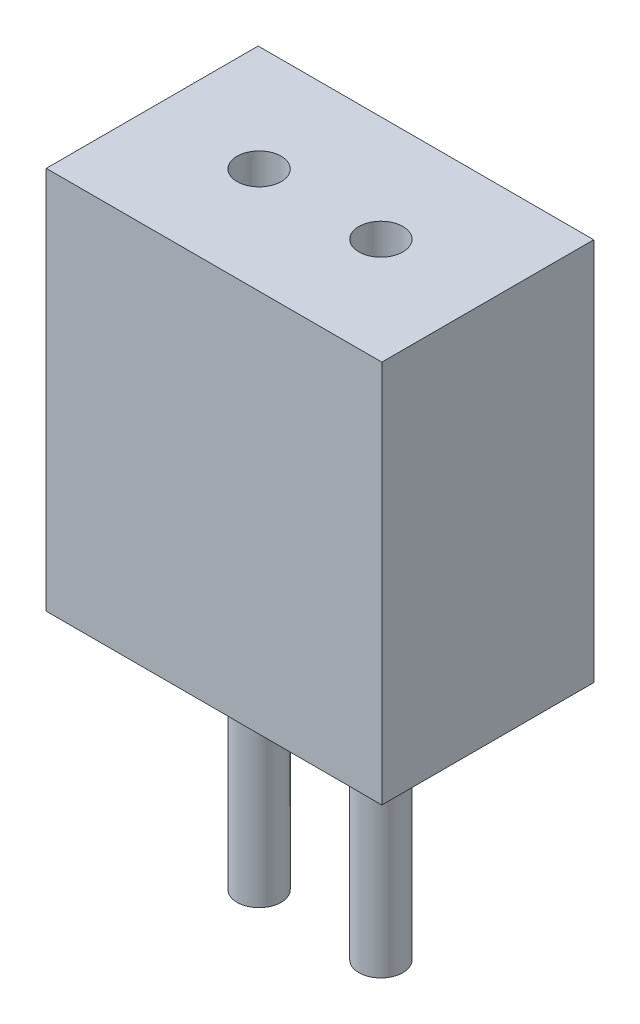
SolidWorks part; units mm, degrees
ref_plane "Front Plane" through (0, 0, 0) normal (0, 0, 1) x (1, 0, 0)
ref_plane "Top Plane" through (0, 0, 0) normal (0, 1, 0) x (1, 0, 0)
ref_plane "Right Plane" through (0, 0, 0) normal (1, 0, 0) x (0, 0, -1)
sketch "Sketch1" plane through (0, 0, 0) normal (0, 1, 0) x (1, 0, 0)
  line L1 (0, 0) -> (3.5, 0)
  line L2 (0, 0) -> (0, 2.21)
  line L3 (0, 2.21) -> (3.5, 2.21)
  line L4 (3.5, 0) -> (3.5, 2.21)
  dimension "D1" = 2.21
  dimension "D2" = 3.5
extrude "Boss-Extrude1" add sketch "Sketch1" along normal blind 4
sketch "Sketch2" plane through (0, 0, 0) normal (0, -1, 0) x (1, 0, 0)
  line L0 (1.75, 0) -> (1.75, -2.21) construction
  line L1 (0, 0) -> (3.5, 0) construction
  line L2 (3.5, -2.21) -> (0, -2.21) construction
  line L3 (0, -1.105) -> (3.5, -1.105) construction
  line L4 (0, -2.21) -> (0, 0) construction
  line L5 (3.5, 0) -> (3.5, -2.21) construction
  circle A0 centre (1.115, -1.105) radius 0.23
  circle A1 centre (2.385, -1.105) radius 0.23
  point P16 (4.6334, -1.105)
  dimension "D2" = 0.46
  dimension "D1" = 1.27
  dimension "D3" = 0.635
extrude "Boss-Extrude2" add sketch "Sketch2" along normal blind 2.51
sketch "Sketch3" plane through (0, 4, 0) normal (0, 1, 0) x (1, 0, 0)
  circle A0 centre (2.385, 1.105) radius 0.23 construction
  circle A1 centre (1.115, 1.105) radius 0.23 construction
  circle A2 centre (2.385, 1.105) radius 0.23
  circle A3 centre (1.115, 1.105) radius 0.23
extrude "Cut-Extrude1" cut sketch "Sketch3" against normal blind 2.51
equation "\"D3@Sketch2\"=\"D1@Sketch2\"/2"
